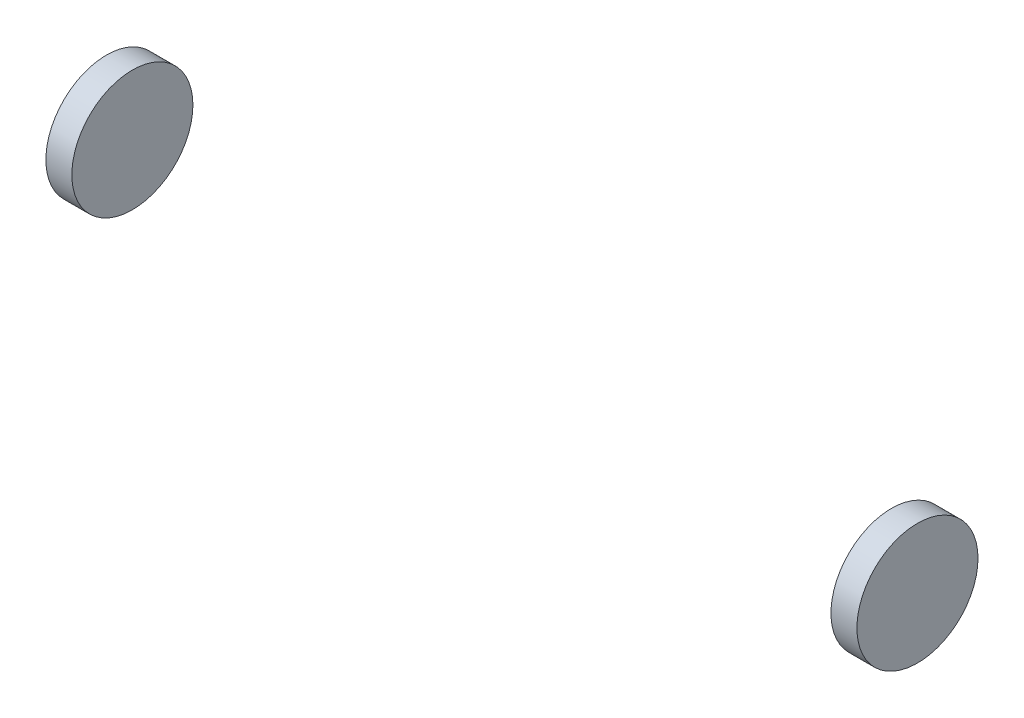
SolidWorks part; units mm, degrees
ref_plane "Front Plane" through (0, 0, 0) normal (0, 0, 1) x (1, 0, 0)
ref_plane "Top Plane" through (0, 0, 0) normal (0, 1, 0) x (1, 0, 0)
ref_plane "Right Plane" through (0, 0, 0) normal (1, 0, 0) x (0, 0, -1)
sketch "Sketch1" plane through (0, 0, 0) normal (1, 0, 0) x (0, 0, -1)
  circle A0 centre (0, 0) radius 140
extrude "Boss-Extrude1" add sketch "Sketch1" along normal blind 60 from offset 937.7127
sketch "Sketch2" plane through (0, 0, 0) normal (1, 0, 0) x (0, 0, -1)
  circle A0 centre (0, 0) radius 140
extrude "Boss-Extrude2" add sketch "Sketch2" along normal blind 60 from offset 877.7127
